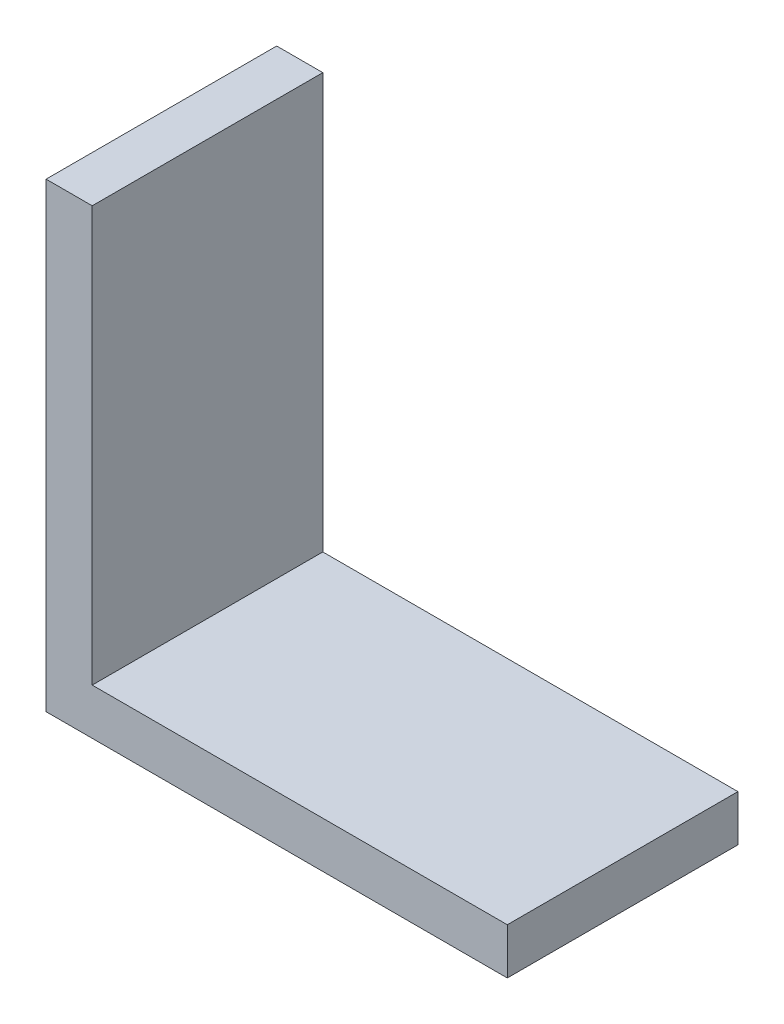
SolidWorks part; units mm, degrees
material "1.4301 (X5CrNi18-10)"
ref_plane "Vorne" through (0, 0, 0) normal (0, 0, 1) x (1, 0, 0)
ref_plane "Oben" through (0, 0, 0) normal (0, 1, 0) x (1, 0, 0)
ref_plane "Rechts" through (0, 0, 0) normal (1, 0, 0) x (0, 0, -1)
sketch "Skizze1" plane through (0, 0, 0) normal (0, 0, 1) x (1, 0, 0)
  line L0 (0, 40) -> (0, 0)
  line L1 (0, 0) -> (40, 0)
  dimension "D1" = 40
  dimension "D2" = 40
extrude "Linear-Austragen-Dünn1" add sketch "Skizze1" along normal mid plane 20 thin thin type one direction reverse wall 4
sketch "Skizze6" plane through (0, 4, 0) normal (0, 1, 0) x (1, 0, 0)
  line L1 (12, 0) -> (33, 0) construction
  line L2 (12, 3.5) -> (33, 3.5)
  line L3 (12, -3.5) -> (33, -3.5)
  line L4 (0, -10) -> (0, 10) construction
  arc A2 (12, 3.5) -> (12, -3.5) centre (12, 0) ccw
  arc A3 (33, -3.5) -> (33, 3.5) centre (33, 0) ccw
  point P9 (22.5, 0)
  dimension "D1" = 12
  dimension "D2" = 33
  dimension "D3" = 21
  dimension "D4" = 7
extrude "Linear austragen2" [suppressed] cut sketch "Skizze6" against normal through all
hole_wizard "Ø7.0 (7) Durchmesser Bohrung1" [suppressed] positions "Skizze8" profile "Skizze7" hole size "Ø7.0" standard "DIN"
sketch "Skizze8" plane through (0, 0, 0) normal (-1, 0, 0) x (0, 0, 1)
  line L0 (10, 0) -> (-10, 0) construction
  point P0 (0, 28)
  dimension "D1" = 28
sketch "Skizze7" plane through (0, 28, 0) normal (0, 1, 0) x (0, 0, 1)
  line L0 (0, 0) -> (0, 14.103)
  line L1 (0, 14.103) -> (3.5, 12)
  line L2 (3.5, 12) -> (3.5, 0)
  line L5 (3.5, 0) -> (0, 0)
  line L10 (0, 14.103) -> (-3.5, 12) construction
  line L11 (0, -6.35) -> (0, 107.95) construction
  dimension "Bohrerdurchmesser" = 7
  dimension "Bohrungstiefe" = 12
  dimension "Spitzenwinkel" = 118
